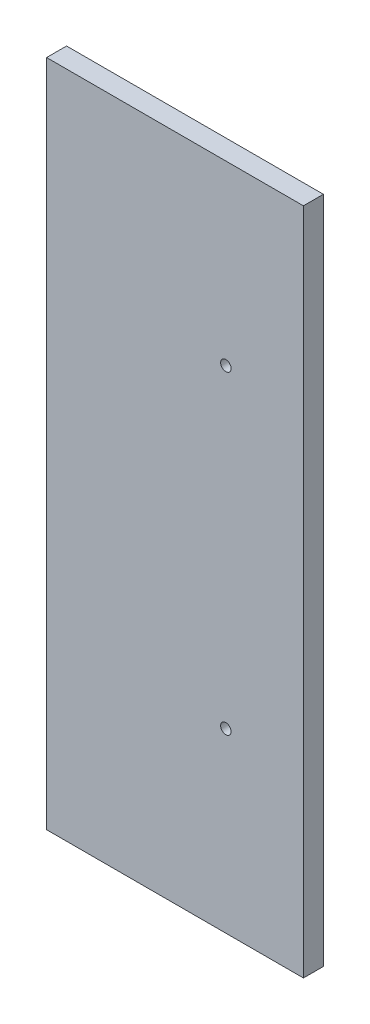
SolidWorks part; units mm, degrees
ref_plane "Front Plane" through (0, 0, 0) normal (0, 0, 1) x (1, 0, 0)
ref_plane "Top Plane" through (0, 0, 0) normal (0, 1, 0) x (1, 0, 0)
ref_plane "Right Plane" through (0, 0, 0) normal (1, 0, 0) x (0, 0, -1)
sketch "Sketch1" plane through (0, 0, 0) normal (0, 0, 1) x (1, 0, 0)
  line L1 (-245.05, 0) -> (0, 0)
  line L2 (-245.05, 0) -> (-245.05, -638.1)
  line L3 (-245.05, -638.1) -> (0, -638.1)
  line L4 (0, 0) -> (0, -638.1)
  dimension "D1" = 638.1
  dimension "D2" = 245.05
extrude "Boss-Extrude1" add sketch "Sketch1" along normal blind 19.05
hole_wizard "Ø10.0mm Dowel Hole1" positions "Sketch2" profile "Sketch3" hole size "Ø10.0" standard "ANSI Metric"
sketch "Sketch2" plane through (0, 0, 0) normal (0, 0, -1) x (-1, 0, 0)
  point P0 (74, -469.05)
  point P3 (74, -169.05)
sketch "Sketch3" plane through (-74, -469.05, 0) normal (1, 0, 0) x (0, 1, 0)
  line L0 (0, 0) -> (0, 30)
  line L1 (0, 30) -> (5, 26.9957)
  line L2 (5, 26.9957) -> (5, 0)
  line L5 (5, 0) -> (0, 0)
  line L10 (0, 30) -> (-5, 26.9957) construction
  line L11 (0, -6.35) -> (0, 107.95) construction
  dimension "Hole Dia." = 10
  dimension "Hole Depth" = 30
  dimension "Drill Angle" = 118
